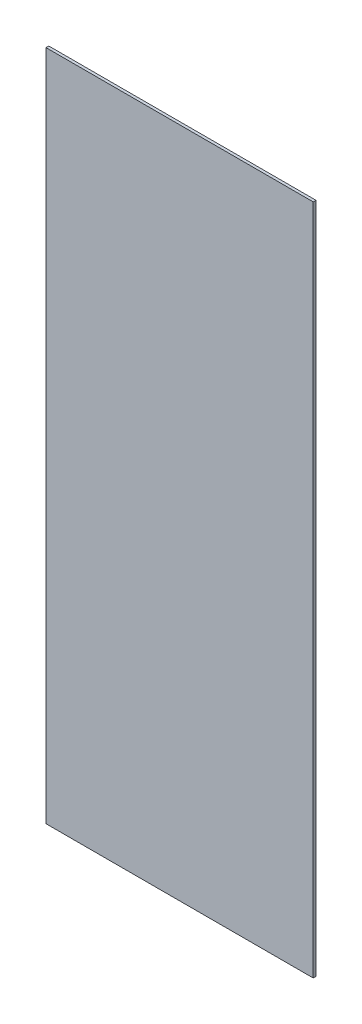
SolidWorks part; units mm, degrees
ref_plane "Front Plane" through (0, 0, 0) normal (0, 0, 1) x (1, 0, 0)
ref_plane "Top Plane" through (0, 0, 0) normal (0, 1, 0) x (1, 0, 0)
ref_plane "Right Plane" through (0, 0, 0) normal (1, 0, 0) x (0, 0, -1)
sketch "Sketch2" plane through (0, 0, 0) normal (0, 0, 1) x (1, 0, 0)
  line L0 (1010.4898, -469.7639) -> (1010.4898, -1081.9039)
  line L1 (1010.4898, -1081.9039) -> (767.1578, -1081.9039)
  line L3 (767.1578, -1081.9039) -> (767.1578, -469.7639)
  line L5 (767.1578, -469.7639) -> (1010.4898, -469.7639)
  dimension "D1" = 243.332
  dimension "D2" = 612.14
extrude "Boss-Extrude1" add sketch "Sketch2" along normal blind 2.54
sketch "Sketch3" plane through (0, 0, 2.54) normal (0, 0, 1) x (1, 0, 0)
  line L0 (888.8238, -469.7639) -> (888.8238, -1081.9039) construction
  line L1 (1010.4898, -469.7639) -> (767.1578, -469.7639) construction
  line L2 (767.1578, -1081.9039) -> (1010.4898, -1081.9039) construction
